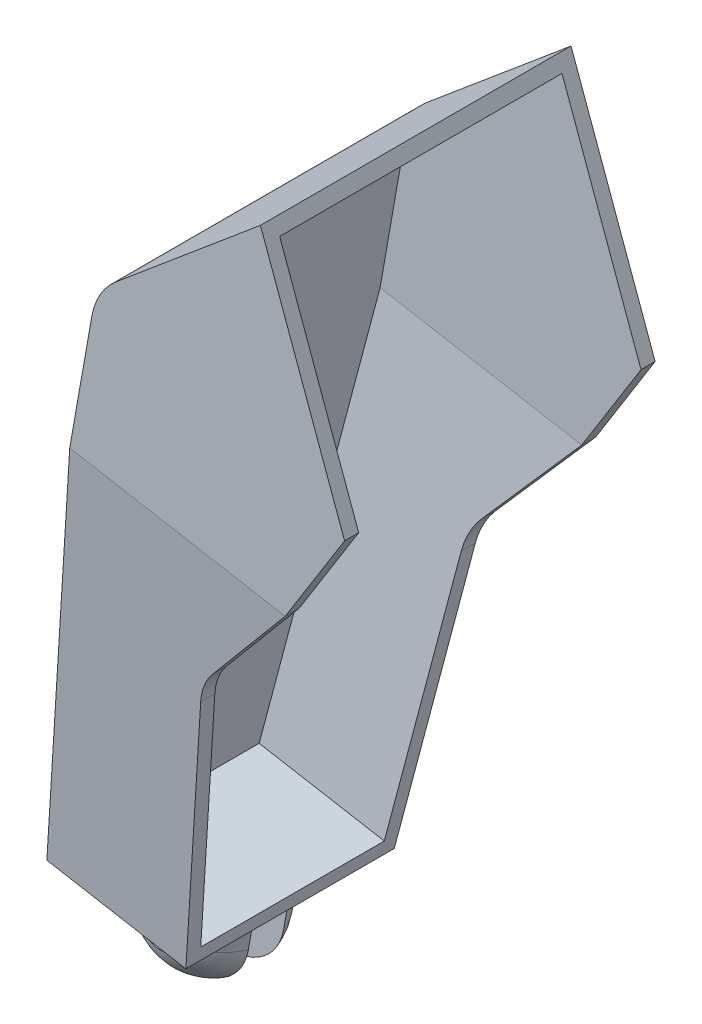
SolidWorks part; units mm, degrees
ref_plane "前视基准面" through (0, 0, 0) normal (0, 0, 1) x (1, 0, 0)
ref_plane "上视基准面" through (0, 0, 0) normal (0, 1, 0) x (1, 0, 0)
ref_plane "右视基准面" through (0, 0, 0) normal (1, 0, 0) x (0, 0, -1)
other "Configuration Table"
sketch "草图1" plane through (0, 0, 0) normal (0, 0, 1) x (1, 0, 0)
  line L1 (14.2295, 51.2992) -> (-6.2397, 34.1235)
  line L2 (-9.6599, 28.1995) -> (-22.9197, -47.0007)
  line L5 (14.9574, 49.2992) -> (-4.3965, 33.0593)
  line L6 (14.2295, 51.2992) -> (14.9574, 49.2992)
  line L7 (-22.9197, -47.0007) -> (-20.9501, -47.348)
  line L8 (-7.8167, 27.1354) -> (-20.9501, -47.348)
  arc A0 (-9.6599, 28.1995) -> (-6.2397, 34.1235) centre (0.1882, 26.4631) cw
  arc A2 (-7.8167, 27.1354) -> (-4.3965, 33.0593) centre (2.0314, 25.3989) cw
  point P6 (-9.0279, 31.7839)
  point P9 (17.0176, 53.6387)
  dimension "D6" = 10
  dimension "D9" = 10
  dimension "D2" = 34
  dimension "D4" = 140
  dimension "D5" = 80
  dimension "D8" = 2
extrude "凸台-拉伸1" add sketch "草图1" along normal mid plane 40 contours L5 A2 L8 L7 L2 A0 L1 L6
sketch "草图3" plane through (-14.191, 2.5023, 0) normal (-0.9848, 0.1736, 0) x (0, 0, 1)
  line L0 (13, -50.2666) -> (20, -50.2666)
  line L2 (20, 26.0937) -> (20, -50.2666) construction
  line L3 (20, 8.0937) -> (13, -50.2666)
  line L4 (20, -50.2666) -> (-20, -50.2666) construction
  line L5 (20, -50.2666) -> (20, 8.0937)
  line L6 (20, 26.0937) -> (-20, 26.0937) construction
  dimension "D1" = 18
  dimension "D2" = 7
extrude "切除-拉伸1" cut sketch "草图3" against normal up to surface (2 mm away) contours L3 L0 L5 up to face at (-14.3834, -10.1063, 0)
mirror "镜向1" about plane through (0, 0, 0) normal (0, 0, 1) of "切除-拉伸1"
sketch "草图4" plane through (0, 0, 20) normal (0, 0, 1) x (1, 0, 0)
  line L2 (-12.7856, 10.473) -> (17.7435, 5.0899)
  line L3 (-9.6599, 28.1995) -> (-12.7856, 10.473) construction
  line L4 (14.2295, 51.2992) -> (-6.2397, 34.1235) construction
  line L6 (-9.6599, 28.1995) -> (-12.7856, 10.473)
  line L7 (14.2295, 51.2992) -> (-6.2397, 34.1235)
  line L9 (26.1511, 18.5449) -> (17.7435, 5.0899)
  line L10 (14.2295, 51.2992) -> (26.1511, 18.5449)
  line L11 (14.2295, 51.2992) -> (14.9574, 49.2992) construction
  arc A0 (-6.2397, 34.1235) -> (-9.6599, 28.1995) centre (0.1882, 26.4631) ccw construction
  arc A2 (-6.2397, 34.1235) -> (-9.6599, 28.1995) centre (0.1882, 26.4631) ccw
  dimension "D3" = 31
extrude "凸台-拉伸2" add sketch "草图4" along normal blind 2
sketch "草图5" plane through (-14.191, 2.5023, 0) normal (-0.9848, 0.1736, 0) x (0, 0, 1)
  line L0 (22, 8.0937) -> (15, -50.2666)
  line L1 (20, 8.0937) -> (13, -50.2666) construction
  line L3 (22, 8.0937) -> (20, 8.0937) construction
  line L4 (20, 8.0937) -> (13, -50.2666)
  line L5 (22, 8.0937) -> (20, 8.0937)
  line L6 (13, -50.2666) -> (15, -50.2666)
extrude "凸台-拉伸3" add sketch "草图5" against normal blind 33
mirror "镜向3" about plane through (0, 0, 0) normal (0, 0, 1) of "凸台-拉伸3", "凸台-拉伸2"
sketch "草图8" plane through (0, 0, 0) normal (0, 0, 1) x (1, 0, 0)
  line L0 (17.7435, 5.0899) -> (5.4946, -9.1263)
  line L1 (3.2223, -13.9172) -> (-3.2236, -50.4736)
  line L2 (9.5789, -52.7311) -> (-22.9197, -47.0007) construction
  line L3 (-3.2236, -50.4736) -> (21.879, -54.8999)
  line L4 (21.879, -54.8999) -> (32.0131, 2.5738)
  line L5 (32.0131, 2.5738) -> (17.7435, 5.0899)
  line L6 (-22.9197, -47.0007) -> (-12.7856, 10.473) construction
  line L8 (-9.6599, 28.1995) -> (-12.7856, 10.473) construction
  arc A0 (3.2223, -13.9172) -> (5.4946, -9.1263) centre (13.0704, -15.6537) cw
  dimension "D2" = 10
  dimension "D1" = 20
extrude "切除-拉伸4" cut sketch "草图8" against normal mid plane 45 contours L5 L0 A0 L1 L3 L4
sketch "草图10" plane through (-14.191, 2.5023, 0) normal (-0.9848, 0.1736, 0) x (0, 0, 1)
  line L0 (-15, -50.2666) -> (15, -50.2666)
  line L1 (-14.7601, -52.2666) -> (14.7601, -52.2666)
  line L2 (15, -50.2666) -> (14.7601, -52.2666)
  line L4 (-15, -50.2666) -> (-14.7601, -52.2666)
  line L6 (15, -50.2666) -> (22, 8.0937) construction
  line L7 (-15, -50.2666) -> (-22, 8.0937) construction
  dimension "D1" = 2
extrude "凸台-拉伸5" add sketch "草图10" against normal up to surface (20 mm away) up to face at (-0.0006, -32.1954, 16.2262)
sketch "草图11" plane through (-9.076, -51.4725, 0) normal (-0.1736, -0.9848, 0) x (0.9848, -0.1736, 0)
  line L0 (-4.4099, 14.7601) -> (-4.4099, -14.7601) construction
  line L1 (5.5901, 14.7601) -> (-14.4099, 14.7601) construction
  line L2 (5.5901, -14.7601) -> (-14.4099, -14.7601) construction
  line L3 (-14.4099, 0) -> (5.5901, 0) construction
  line L4 (-14.4099, -14.7601) -> (-14.4099, 14.7601) construction
  line L5 (5.5901, 14.7601) -> (5.5901, -14.7601) construction
  circle A0 centre (-4.4099, 0) radius 8
  point P15 (-4.4099, 0)
extrude "凸台-拉伸6" add sketch "草图11" along normal blind 6
sketch "草图12" plane through (0, 0, 0) normal (0, 0, 1) x (1, 0, 0)
  line L0 (-22.3393, -55.2264) -> (-6.5824, -58.0048) construction
  line L1 (-14.4608, -56.6156) -> (-6.5824, -58.0048)
  line L2 (-14.4608, -56.6156) -> (-15.85, -64.4941)
  arc A0 (-15.85, -64.4941) -> (-6.5824, -58.0048) centre (-14.4608, -56.6156) ccw
revolve "旋转1" add sketch "草图12" angle 360 about L2
sketch "草图13" plane through (-14.191, 2.5023, 0) normal (-0.9848, 0.1736, 0) x (0, 0, 1)
  line L0 (-8, -52.2666) -> (8, -52.2666) construction
  line L1 (-2.5, -52.2666) -> (2.5, -52.2666)
  line L2 (-2.5, -52.2666) -> (-2.5, -74.3021)
  line L3 (-2.5, -74.3021) -> (2.5, -74.3021)
  line L4 (2.5, -52.2666) -> (2.5, -74.3021)
  line L5 (0, -20.8324) -> (0, 20.8324) construction
  dimension "D1" = 2.5
  dimension "D2" = 2.5
extrude "切除-拉伸5" cut sketch "草图13" against normal blind 40
sketch "草图14" plane through (0, 0, 0) normal (0, 0, 1) x (1, 0, 0)
  line L0 (-6.9769, -57.9352) -> (-21.9447, -55.296) construction
  circle A0 centre (-14.4608, -56.6156) radius 2.5
extrude "切除-拉伸6" cut sketch "草图14" against normal mid plane 40
